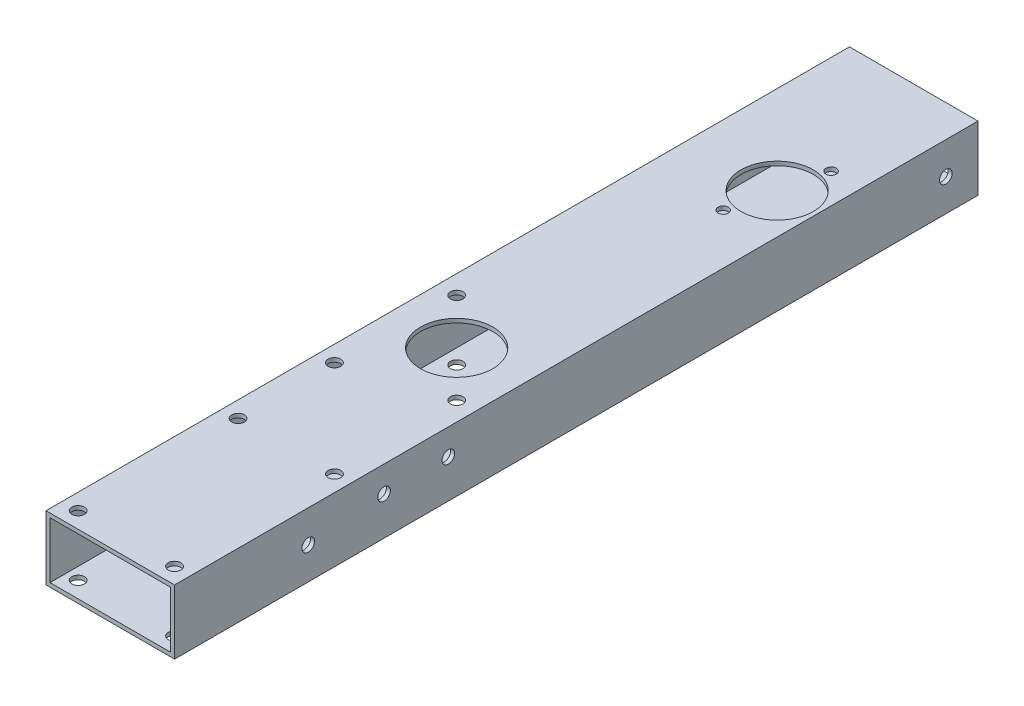
SolidWorks part; units mm, degrees
material "6061 Alloy"
ref_plane "Front Plane" through (0, 0, 0) normal (0, 0, 1) x (1, 0, 0)
ref_plane "Top Plane" through (0, 0, 0) normal (0, 1, 0) x (1, 0, 0)
ref_plane "Right Plane" through (0, 0, 0) normal (1, 0, 0) x (0, 0, -1)
sketch "Sketch1" plane through (0, 0, 0) normal (0, 0, 1) x (1, 0, 0)
  line L0 (-23.8125, 11.1125) -> (23.8125, 11.1125)
  line L2 (-25.4, 12.7) -> (25.4, 12.7)
  line L3 (-25.4, 12.7) -> (-25.4, -12.7)
  line L4 (-25.4, -12.7) -> (25.4, -12.7)
  line L5 (25.4, 12.7) -> (25.4, -12.7)
  line L10 (23.8125, 11.1125) -> (23.8125, -11.1125)
  line L11 (-23.8125, -11.1125) -> (23.8125, -11.1125)
  line L12 (-23.8125, 11.1125) -> (-23.8125, -11.1125)
  point P12 (0, 12.7)
  point P14 (25.4, 0)
  dimension "Wall Thickness" = 1.5875
  dimension "Outside Width" = 50.8
  dimension "Outside Height" = 25.4
  dimension "Inside Height" = 22.225
  dimension "Inside Width" = 47.625
sketch "Sketch2" plane through (0, 0, 0) normal (1, 0, 0) x (0, 0, -1)
  line L0 (158.75, 0) -> (-158.75, 0)
  point P4 (0, 0)
  point P7 (-158.75, 0)
  point P10 (158.75, 0)
  dimension "Length" = 317.5
sketch "Sketch3" plane through (0, 0, 0) normal (0, 0, 1) x (1, 0, 0)
  line L21 (25.4, 12.7) -> (-25.4, 12.7)
  line L22 (25.4, -12.7) -> (25.4, 12.7)
  line L23 (-25.4, -12.7) -> (25.4, -12.7)
  line L24 (-25.4, 12.7) -> (-25.4, -12.7)
  line L25 (25.4, 12.7) -> (-25.4, 12.7)
  line L26 (25.4, -12.7) -> (25.4, 12.7)
  line L27 (-25.4, -12.7) -> (25.4, -12.7)
  line L28 (-25.4, 12.7) -> (-25.4, -12.7)
  line L29 (23.8125, 11.1125) -> (-23.8125, 11.1125)
  line L30 (23.8125, -11.1125) -> (23.8125, 11.1125)
  line L31 (-23.8125, -11.1125) -> (23.8125, -11.1125)
  line L32 (-23.8125, 11.1125) -> (-23.8125, -11.1125)
  line L33 (23.8125, 11.1125) -> (-23.8125, 11.1125)
  line L34 (23.8125, -11.1125) -> (23.8125, 11.1125)
  line L35 (-23.8125, -11.1125) -> (23.8125, -11.1125)
  line L36 (-23.8125, 11.1125) -> (-23.8125, -11.1125)
  dimension "D1" = 0
  dimension "D2" = 0
extrude "Boss-Extrude1" add sketch "Sketch3" along normal up to vertex (158.75 mm away) and the other way up to vertex (158.75 mm away) up to point (0, 0, 158.75) other way up to point (0, 0, -158.75)
sketch "Drawing Reference" plane through (0, 0, 0) normal (1, 0, 0) x (0, 0, -1)
  line L0 (-158.75, 0) -> (158.75, 0) construction
  line L1 (0, -12.7) -> (0, 12.7) construction
  line L2 (-158.75, -12.7) -> (158.75, -12.7) construction
  line L5 (-158.75, 12.7) -> (158.75, 12.7) construction
  point P7 (-122.174, 0)
  point P8 (122.174, 0)
  dimension "D1" = 36.576
sketch "Sketch4" plane through (0, 12.7, 0) normal (0, 1, 0) x (1, 0, 0)
  line L0 (0, 158.75) -> (0, 95.25) construction
  line L1 (25.4, 158.75) -> (-25.4, 158.75) construction
  line L2 (0, 95.25) -> (9.525, 95.25) construction
  line L3 (0, 158.75) -> (0, -26.67) construction
  circle A1 centre (9.525, 95.25) radius 14.2875
  circle A3 centre (9.525, 95.25) radius 117.5004 construction
  circle A4 centre (0, -21.8637) radius 14.2875
  dimension "D1" = 63.5
  dimension "D3" = 235.0008
  dimension "D2" = 9.525
extrude "Cut-Extrude1" cut sketch "Sketch4" against normal blind 39.37
sketch "Sketch6" plane through (0, 12.7, 0) normal (0, 1, 0) x (1, 0, 0)
  line L0 (-17.9605, -3.9032) -> (17.9605, -39.8242) construction
  circle A0 centre (0, -21.8637) radius 25.4 construction
  point P8 (0, -21.8637)
  dimension "D1" = 50.8
hole_wizard "#10 Clearance Hole1" positions "Sketch7" profile "Sketch8" hole size "#10" standard "ANSI Inch" end condition through all
sketch "Sketch7" plane through (0, 12.7, 0) normal (0, 1, 0) x (1, 0, 0)
  point P0 (-17.9605, -3.9032)
  point P3 (17.9605, -39.8242)
sketch "Sketch8" plane through (-17.9605, 12.7, 3.9032) normal (1, 0, 0) x (0, 0, 1)
  line L0 (0, 0) -> (0, 25.4)
  line L1 (0, 25.4) -> (2.4892, 25.4)
  line L2 (2.4892, 25.4) -> (2.4892, 0)
  line L5 (2.4892, 0) -> (0, 0)
  line L11 (0, -6.35) -> (0, 107.95) construction
  dimension "Thru Hole Dia." = 4.9784
  dimension "Thru Hole Depth" = 25.4
sketch "Sketch9" plane through (-25.4, 0, 0) normal (-1, 0, 0) x (0, 0, 1)
  line L0 (75.9497, 2.425) -> (50.5497, 2.425) construction
hole_wizard "#10 Clearance Hole2" positions "Sketch12" profile "Sketch13" hole size "#10" standard "ANSI Inch" end condition through all
sketch "Sketch12" plane through (-25.4, 0, 0) normal (-1, 0, 0) x (0, 0, 1)
  point P0 (50.5497, 2.425)
  point P3 (75.9497, 2.425)
sketch "Sketch13" plane through (-25.4, 2.425, 50.5497) normal (0, 1, 0) x (0, 0, 1)
  line L0 (0, 0) -> (0, 50.8)
  line L1 (0, 50.8) -> (2.4892, 50.8)
  line L2 (2.4892, 50.8) -> (2.4892, 0)
  line L5 (2.4892, 0) -> (0, 0)
  line L11 (0, -6.35) -> (0, 107.95) construction
  dimension "Thru Hole Dia." = 4.9784
  dimension "Thru Hole Depth" = 50.8
hole_wizard "#10 Clearance Hole3" positions "Sketch14" profile "Sketch15" hole size "#10" standard "ANSI Inch" end condition through all
sketch "Sketch14" plane through (0, 12.7, 0) normal (0, 1, 0) x (1, 0, 0)
  point P0 (-19.05, -51.1131)
  point P3 (-19.05, -89.2131)
  point P6 (19.05, -89.2131)
  point P9 (19.05, -152.4)
  point P12 (-19.05, -152.4)
sketch "Sketch15" plane through (-19.05, 12.7, 51.1131) normal (1, 0, 0) x (0, 0, 1)
  line L0 (0, 0) -> (0, 25.4)
  line L1 (0, 25.4) -> (2.4892, 25.4)
  line L2 (2.4892, 25.4) -> (2.4892, 0)
  line L5 (2.4892, 0) -> (0, 0)
  line L11 (0, -6.35) -> (0, 107.95) construction
  dimension "Thru Hole Dia." = 4.9784
  dimension "Thru Hole Depth" = 25.4
hole_wizard "#20 (0.161) Diameter Hole1" positions "Sketch16" profile "Sketch17" hole size "#20" standard "ANSI Inch" end condition through all
sketch "Sketch16" plane through (0, -12.7, 0) normal (0, -1, 0) x (-1, 0, 0)
  point P0 (-5.5254, 77.9257)
  point P3 (-13.5246, 112.5743)
sketch "Sketch17" plane through (5.5254, -12.7, -77.9257) normal (1, 0, 0) x (0, 0, -1)
  line L0 (0, 0) -> (0, 25.4)
  line L1 (0, 25.4) -> (2.0447, 25.4)
  line L2 (2.0447, 25.4) -> (2.0447, 0)
  line L5 (2.0447, 0) -> (0, 0)
  line L11 (0, -6.35) -> (0, 107.95) construction
  dimension "Thru Hole Dia." = 4.0894
  dimension "Thru Hole Depth" = 25.4
hole_wizard "#10 Clearance Hole4" positions "Sketch18" profile "Sketch19" hole size "#10" standard "ANSI Inch"
sketch "Sketch18" plane through (25.4, 0, 0) normal (1, 0, 0) x (0, 0, -1)
  point P0 (146.05, 0)
  point P3 (-105.918, 0)
sketch "Sketch19" plane through (25.4, 0, -146.05) normal (0, 1, 0) x (0, 0, -1)
  line L0 (0, 0) -> (0, 14.1957)
  line L1 (0, 14.1957) -> (2.4892, 12.7)
  line L2 (2.4892, 12.7) -> (2.4892, 0)
  line L5 (2.4892, 0) -> (0, 0)
  line L10 (0, 14.1957) -> (-2.4892, 12.7) construction
  line L11 (0, -6.35) -> (0, 107.95) construction
  dimension "Hole Dia." = 4.9784
  dimension "Hole Depth" = 12.7
  dimension "Drill Angle" = 118
equation "\"D1@Drawing Reference\"=\"Outside Width@Sketch1\" * 0.72"
